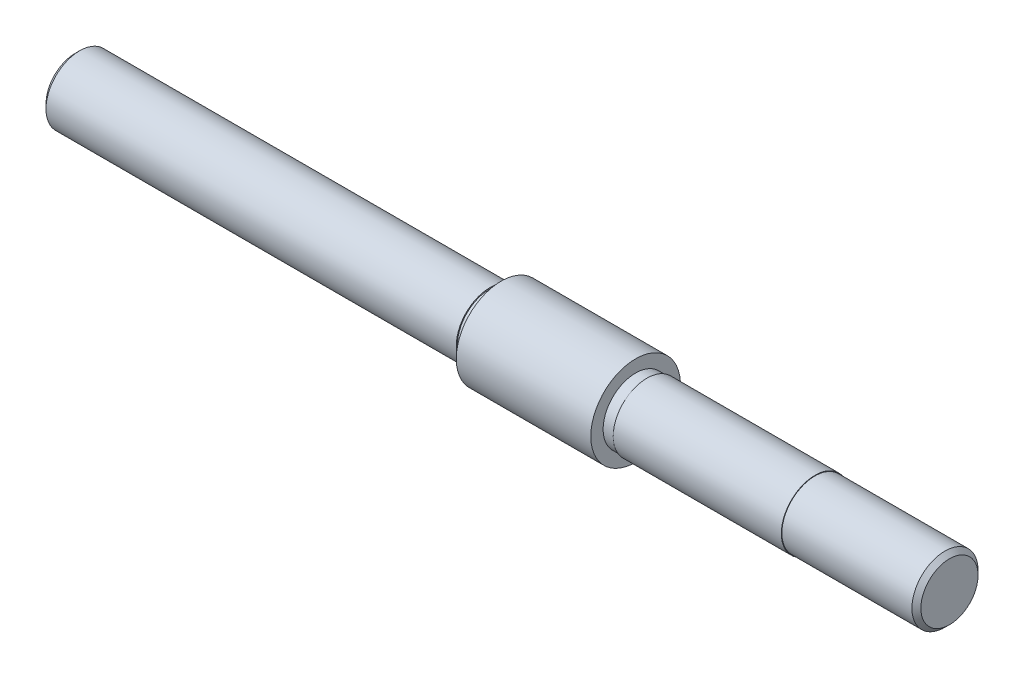
SolidWorks part; units mm, degrees
ref_plane "前视基准面" through (0, 0, 0) normal (0, 0, 1) x (1, 0, 0)
ref_plane "上视基准面" through (0, 0, 0) normal (0, 1, 0) x (1, 0, 0)
ref_plane "右视基准面" through (0, 0, 0) normal (1, 0, 0) x (0, 0, -1)
sketch "草图1" plane through (0, 0, 0) normal (0, 0, 1) x (1, 0, 0)
  line L0 (-12.0888, 0) -> (5.2383, 0) construction
  line L1 (0, 9.0788) -> (0, -9.2095) construction
  line L2 (0, 0) -> (0, 1.475)
  line L3 (0, 1.475) -> (-6, 1.475)
  line L4 (-6, 1.475) -> (-6, 1.5)
  line L5 (-6, 1.5) -> (-13.5, 1.5)
  line L6 (-14, 1.45) -> (-14, 2)
  line L7 (-14, 2) -> (-20, 2)
  line L8 (-20, 2) -> (-20, 1.45)
  line L9 (-20.5, 1.5) -> (-39, 1.5)
  line L10 (-39, 1.5) -> (-39, 0)
  line L11 (-39, 0) -> (0, 0)
  line L12 (-13.5, 1.5) -> (-13.5, 1.45)
  line L13 (-13.5, 1.45) -> (-14, 1.45)
  line L14 (-20.5, 1.5) -> (-20.5, 1.45)
  line L15 (-20.5, 1.45) -> (-20, 1.45)
  dimension "D1" = 2.95
  dimension "D2" = 3
  dimension "D3" = 3
  dimension "D4" = 4
  dimension "D5" = 6
  dimension "D6" = 0.05
  dimension "D7" = 39
  dimension "D8" = 6
  dimension "D9" = 25
  dimension "D10" = 0.5
  dimension "D11" = 0.5
  dimension "D12" = 0.05
  dimension "D13" = 14
revolve "旋转1" add sketch "草图1" angle 360 about L0
cosmetic thread "装饰螺纹线1" parameters "D2"=2.013
chamfer "倒角1" distance 0.2 angle 45 2 edges at (-39, 0, 1.5) (0, 0, 1.475)
